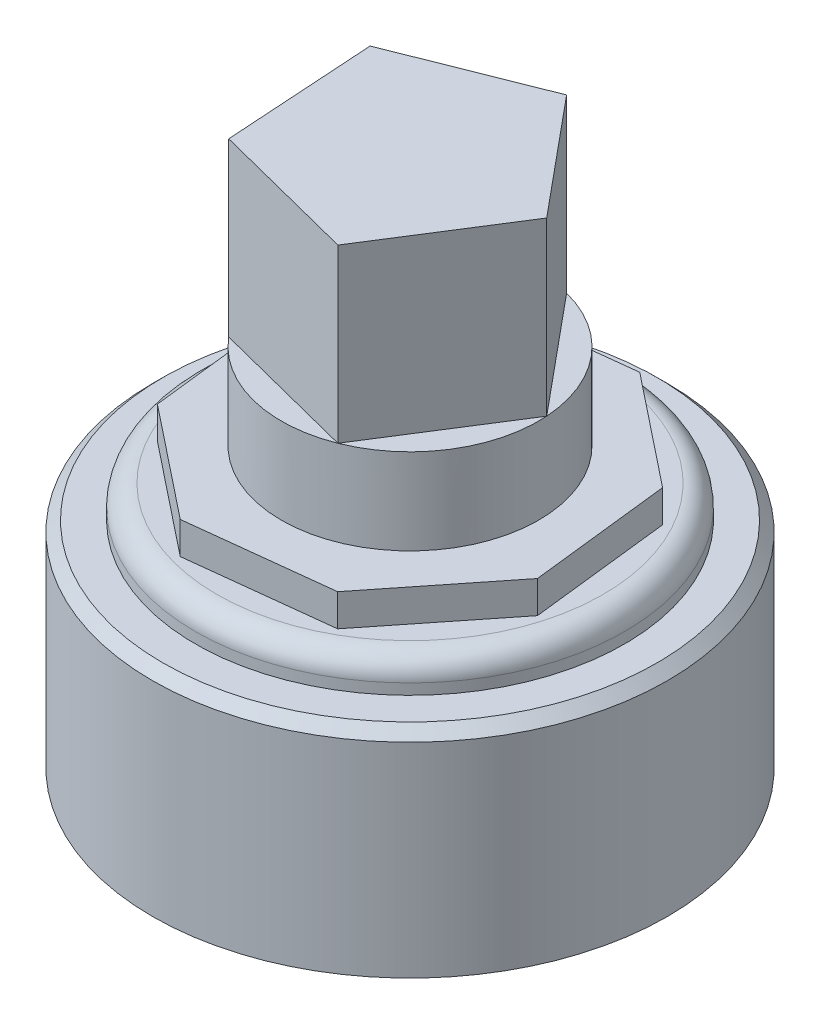
SolidWorks part; units mm, degrees
ref_plane "Front Plane" through (0, 0, 0) normal (0, 0, 1) x (1, 0, 0)
ref_plane "Top Plane" through (0, 0, 0) normal (0, 1, 0) x (1, 0, 0)
ref_plane "Right Plane" through (0, 0, 0) normal (1, 0, 0) x (0, 0, -1)
sketch "Sketch1" plane through (0, 0, 0) normal (0, 1, 0) x (1, 0, 0)
  circle A0 centre (0, 0) radius 38.1
  dimension "D1" = 76.2
extrude "Boss-Extrude1" add sketch "Sketch1" against normal blind 31.75
chamfer "Chamfer1" distance 1.524 angle 45 1 edges at (0, 0, 38.1)
sketch "Sketch2" plane through (0, 0, 0) normal (0, 1, 0) x (1, 0, 0)
  circle A0 centre (0, 0) radius 31.75
  dimension "D1" = 63.5
extrude "Boss-Extrude3" add sketch "Sketch2" along normal mid plane 9.525 contours A0
sketch "Sketch4" plane through (0, 0, 0) normal (0, 1, 0) x (1, 0, 0)
  line L1 (7.571, 26.4297) -> (-13.3351, 24.0422)
  line L2 (-13.3351, 24.0422) -> (-26.4297, 7.571)
  line L3 (-26.4297, 7.571) -> (-24.0422, -13.3351)
  line L4 (-24.0422, -13.3351) -> (-7.571, -26.4297)
  line L5 (-7.571, -26.4297) -> (13.3351, -24.0422)
  line L6 (13.3351, -24.0422) -> (26.4297, -7.571)
  line L7 (26.4297, -7.571) -> (24.0422, 13.3351)
  line L8 (24.0422, 13.3351) -> (7.571, 26.4297)
  circle A0 centre (0, 0) radius 25.4 construction
  dimension "D1" = 50.8
extrude "Boss-Extrude4" add sketch "Sketch4" along normal blind 9.525
sketch "Sketch5" plane through (0, 9.525, 0) normal (0, 1, 0) x (1, 0, 0)
  circle A0 centre (0, 0) radius 19.05
  dimension "D1" = 38.1
extrude "Boss-Extrude5" add sketch "Sketch5" along normal blind 12.7
sketch "Sketch6" plane through (0, 22.225, 0) normal (0, 1, 0) x (1, 0, 0)
  line L6 (4.7167, 18.4568) -> (-16.0959, 10.1894)
  line L7 (-16.0959, 10.1894) -> (-14.6646, -12.1595)
  line L8 (-14.6646, -12.1595) -> (7.0327, -17.7043)
  line L9 (7.0327, -17.7043) -> (19.011, 1.2176)
  line L10 (19.011, 1.2176) -> (4.7167, 18.4568)
  circle A0 centre (0, 0) radius 15.4118 construction
extrude "Boss-Extrude6" add sketch "Sketch6" along normal blind 25.4
fillet "Fillet2" radius 3.175 1 edges at (0, 4.7625, 31.75)
